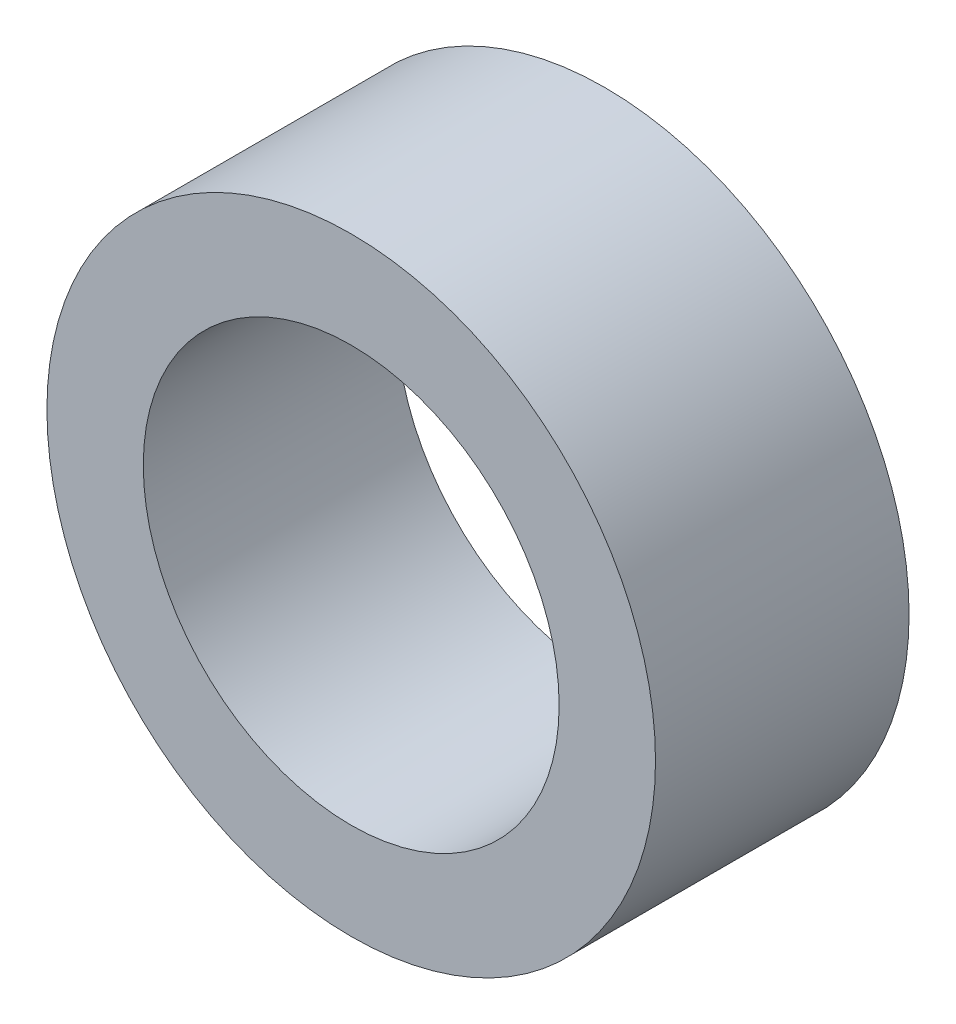
SolidWorks part; units mm, degrees
ref_plane "Front Plane" through (0, 0, 0) normal (0, 0, 1) x (1, 0, 0)
ref_plane "Top Plane" through (0, 0, 0) normal (0, 1, 0) x (1, 0, 0)
ref_plane "Right Plane" through (0, 0, 0) normal (1, 0, 0) x (0, 0, -1)
sketch "Sketch1" plane through (0, 0, 0) normal (0, 0, 1) x (1, 0, 0)
  line L3 (0, 0) -> (0, 6) construction
  circle A0 centre (0, 0) radius 4.1
  circle A1 centre (0, 0) radius 6
  dimension "D1" = 8.2
  dimension "D2" = 12
extrude "Boss-Extrude1" add sketch "Sketch1" along normal blind 5
